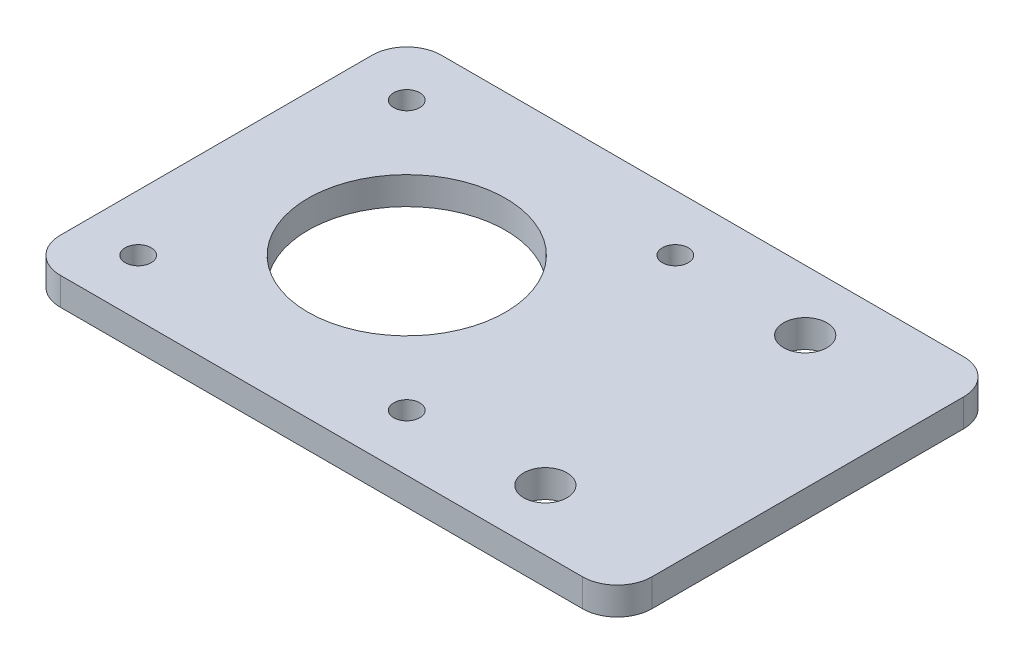
SolidWorks part; units mm, degrees
ref_plane "Front Plane" through (0, 0, 0) normal (0, 0, 1) x (1, 0, 0)
ref_plane "Top Plane" through (0, 0, 0) normal (0, 1, 0) x (1, 0, 0)
ref_plane "Right Plane" through (0, 0, 0) normal (1, 0, 0) x (0, 0, -1)
sketch "Sketch1" plane through (0, 0, 0) normal (0, 1, 0) x (1, 0, 0)
  line L1 (-34.15, 22) -> (34.15, 22)
  line L2 (-34.15, 22) -> (-34.15, -22)
  line L3 (-34.15, -22) -> (34.15, -22)
  line L4 (34.15, 22) -> (34.15, -22)
  line L5 (-34.15, 22) -> (34.15, -22) construction
  line L6 (-34.15, -22) -> (34.15, 22) construction
  point P0 (0, 0)
  dimension "D1" = 44
  dimension "D2" = 68.3
extrude "Boss-Extrude1" add sketch "Sketch1" along normal blind 3.2
sketch "Sketch2" plane through (0, 3.2, 0) normal (0, 1, 0) x (1, 0, 0)
  line L0 (-34.15, 0) -> (34.15, 0) construction
  line L1 (-34.15, 22) -> (-34.15, -22) construction
  line L2 (34.15, -22) -> (34.15, 22) construction
  line L3 (18.85, -15) -> (18.85, 15) construction
  line L5 (-27.65, 15.5) -> (3.35, 15.5) construction
  line L6 (-27.65, 15.5) -> (-27.65, -15.5) construction
  line L7 (-27.65, -15.5) -> (3.35, -15.5) construction
  line L8 (3.35, 15.5) -> (3.35, -15.5) construction
  line L9 (-27.65, 15.5) -> (3.35, -15.5) construction
  line L10 (-27.65, -15.5) -> (3.35, 15.5) construction
  circle A0 centre (-12.15, 0) radius 11.4
  circle A1 centre (18.85, 15) radius 2.5
  circle A2 centre (18.85, -15) radius 2.5
  circle A3 centre (-27.65, 15.5) radius 1.5
  circle A4 centre (3.35, 15.5) radius 1.5
  circle A5 centre (3.35, -15.5) radius 1.5
  circle A6 centre (-27.65, -15.5) radius 1.5
  point P11 (18.85, 0)
  dimension "D1" = 22.8
  dimension "D3" = 5
  dimension "D7" = 3
  dimension "D2" = 22
  dimension "D4" = 30
  dimension "D5" = 15.3
  dimension "D6" = 31
extrude "Cut-Extrude2" cut sketch "Sketch2" against normal through all
fillet "Fillet1" radius 4 4 edges at (34.15, 1.6, 22) (-34.15, 1.6, 22) (-34.15, 1.6, -22) (34.15, 1.6, -22)
